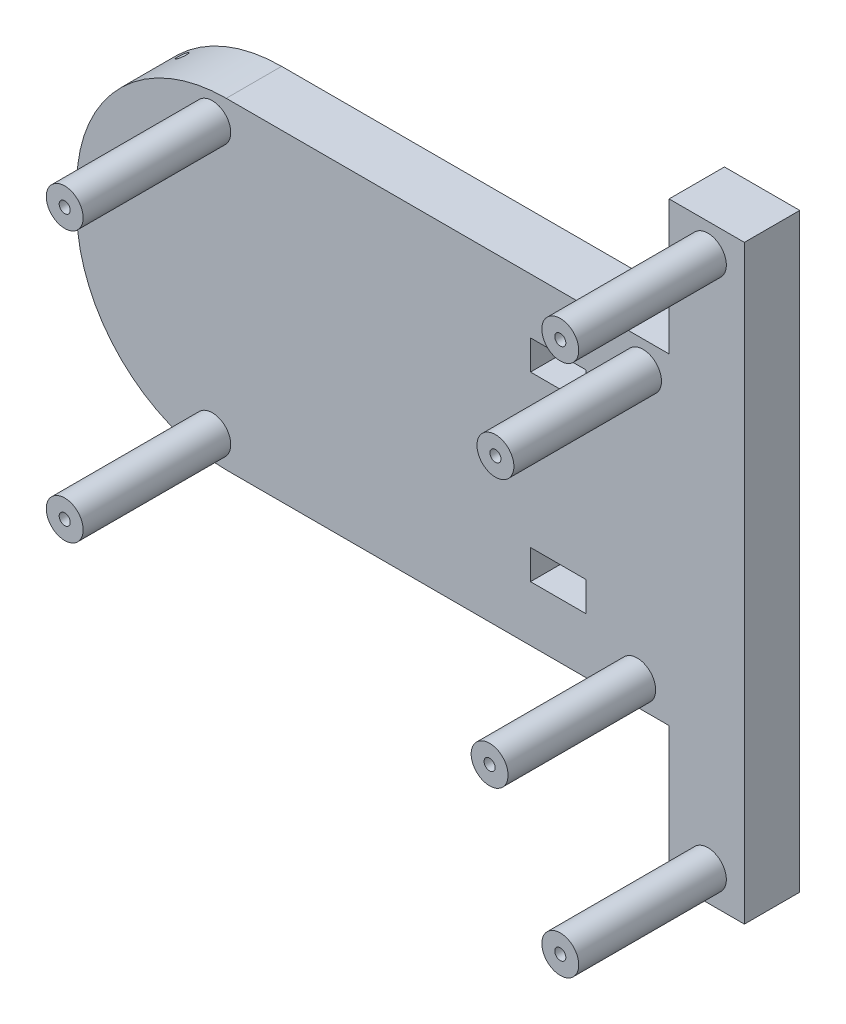
SolidWorks part; units mm, degrees
ref_plane "Plan de face" through (0, 0, 0) normal (0, 0, 1) x (1, 0, 0)
ref_plane "Plan de dessus" through (0, 0, 0) normal (0, 1, 0) x (1, 0, 0)
ref_plane "Plan de droite" through (0, 0, 0) normal (1, 0, 0) x (0, 0, -1)
sketch "Esquisse1" plane through (0, 0, 0) normal (0, 0, 1) x (1, 0, 0)
  line L7 (-20.4048, 60.8522) -> (-20.4048, 43.608)
  line L11 (-42.9128, 28.608) -> (-42.9128, 20.5821)
  line L12 (-42.9128, 20.5821) -> (-57.9614, 20.5821)
  line L13 (-57.9614, 20.5821) -> (-57.9614, 28.608)
  line L15 (-57.9614, 28.608) -> (-42.9128, 28.608)
  line L16 (-20.4048, 43.608) -> (-140.4048, 43.608)
  line L25 (-20.4048, 60.8522) -> (-20.4048, 80)
  line L27 (0, 80) -> (-20.4048, 80)
  line L33 (0, -80) -> (0, 80)
  line L34 (-57.9614, -20.5821) -> (-57.9614, -28.608)
  line L35 (-42.9128, -20.5821) -> (-57.9614, -20.5821)
  line L36 (-42.9128, -28.608) -> (-42.9128, -20.5821)
  line L37 (-57.9614, -28.608) -> (-42.9128, -28.608)
  line L38 (-20.4048, -43.608) -> (-140.4048, -43.608)
  line L39 (-20.4048, -60.8522) -> (-20.4048, -43.608)
  line L40 (-20.4048, -60.8522) -> (-20.4048, -80)
  line L41 (0, -80) -> (-20.4048, -80)
  arc A0 (-140.4048, 43.608) -> (-180.7891, 0) centre (-140.4048, 3.1046) ccw
  arc A1 (-140.4048, -43.608) -> (-180.7891, 0) centre (-140.4048, -3.1046) cw
  dimension "D2" = 120
extrude "Boss.-Extru.2" add sketch "Esquisse1" along normal blind 15
ref_plane "Plan1" through (-170.1225, 30.6253, 0) normal (-0.7337, 0.6795, 0) x (0, 0, 1)
sketch "Esquisse2" plane through (-170.1225, 30.6253, 0) normal (-0.7337, 0.6795, 0) x (0, 0, 1)
  line L0 (15, -29.7176) -> (0, -29.7176) construction
  circle A1 centre (3.5667, 8.2824) radius 1.5
  circle A2 centre (3.5667, -21.7176) radius 1.5
  circle A3 centre (3.5667, -6.7176) radius 1.5
  dimension "D1" = 8
  dimension "D3" = 15
  dimension "D2" = 30
extrude "Enlèv. mat.-Extru.1" cut sketch "Esquisse2" against normal blind 22
ref_plane "Plan2" through (-170.1225, -30.6253, 15) normal (-0.7337, -0.6795, 0) x (0, 0, 1)
sketch "Esquisse7" plane through (-170.1225, -30.6253, 15) normal (-0.7337, -0.6795, 0) x (0, 0, 1)
  line L1 (0, 29.7176) -> (-15, 29.7176) construction
  circle A0 centre (-11.5556, 21.7176) radius 1.5
  circle A1 centre (-11.5556, -8.2824) radius 1.5
  circle A2 centre (-11.5556, 6.7176) radius 1.5
  dimension "D1" = 15
  dimension "D2" = 30
  dimension "D3" = 8
extrude "Enlèv. mat.-Extru.2" cut sketch "Esquisse7" against normal blind 22
sketch "Esquisse8" plane through (0, 0, 15) normal (0, 0, 1) x (1, 0, 0)
  circle A0 centre (-9.8906, 72.2136) radius 1.5
  circle A1 centre (-9.8906, 72.2136) radius 5
  circle A2 centre (-9.8906, -71.9919) radius 1.5
  circle A3 centre (-9.8906, -71.9919) radius 5
  circle A4 centre (-27.4656, 36.1622) radius 1.5
  circle A5 centre (-27.4656, 36.1622) radius 5
  circle A6 centre (-29.0429, -37.0671) radius 1.5
  circle A7 centre (-29.0429, -37.0671) radius 5
  circle A12 centre (-144.182, 36.1622) radius 1.5
  circle A13 centre (-144.182, 36.1622) radius 5
  circle A14 centre (-144.182, -37.0671) radius 1.5
  circle A15 centre (-144.182, -37.0671) radius 5
  point P3 (0, 0)
  point P4 (0, 0)
extrude "Boss.-Extru.3" add sketch "Esquisse8" along normal blind 40
